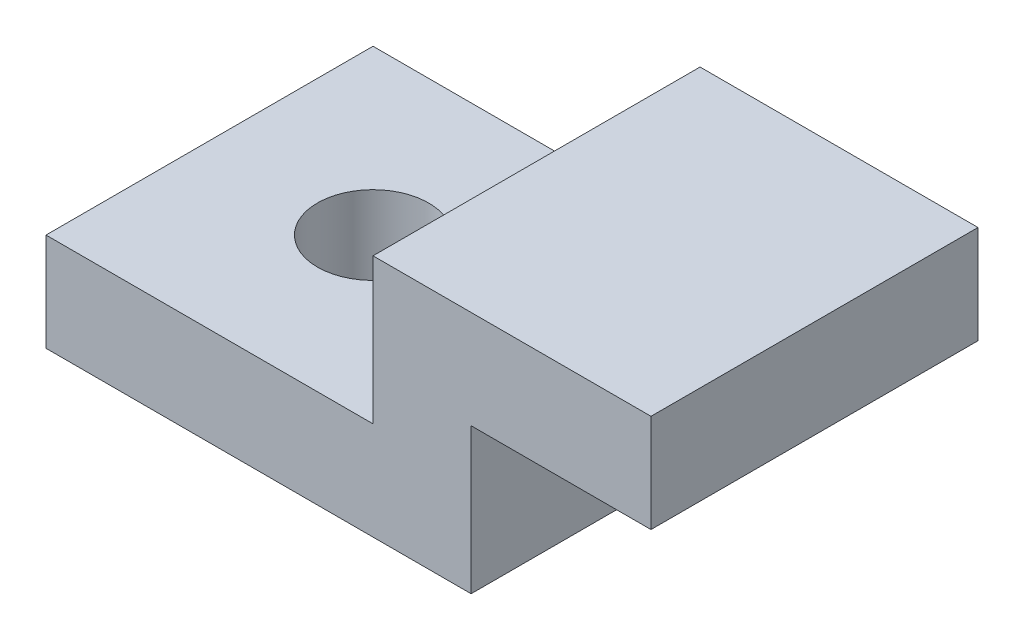
SolidWorks part; units mm, degrees
ref_plane "Front Plane" through (0, 0, 0) normal (0, 0, 1) x (1, 0, 0)
ref_plane "Top Plane" through (0, 0, 0) normal (0, 1, 0) x (1, 0, 0)
ref_plane "Right Plane" through (0, 0, 0) normal (1, 0, 0) x (0, 0, -1)
sketch "Sketch1" plane through (0, 0, 0) normal (0, 0, 1) x (1, 0, 0)
  line L1 (0, 0) -> (0, 4.45)
  line L2 (0, 4.45) -> (5.5, 4.45)
  line L3 (5.5, 4.45) -> (5.5, 7.45)
  line L4 (5.5, 7.45) -> (-3, 7.45)
  line L5 (-3, 7.45) -> (-3, 3)
  line L8 (-3, 0) -> (0, 0)
  line L9 (-3, 0) -> (-13, 0)
  line L10 (-13, 0) -> (-13, 3)
  line L11 (-13, 3) -> (-3, 3)
  dimension "D1" = 4.45
  dimension "D2" = 5.5
  dimension "D3" = 10
  dimension "D4" = 3
  dimension "D5" = 3
  dimension "D6" = 3
extrude "Boss-Extrude1" add sketch "Sketch1" along normal mid plane 10
sketch "Sketch2" plane through (0, 3, 0) normal (0, 1, 0) x (1, 0, 0)
  line L0 (-3, 5) -> (-13, 5) construction
  line L1 (-13, -5) -> (-13, 5) construction
  point P0 (-8, 0)
  point P3 (-8, 5)
  point P4 (0, 0)
  point P7 (-13, 0)
hole_wizard "M3 Clearance Hole1" positions "Sketch3" profile "Sketch4" hole size "M3" standard "ANSI Metric" end condition through all
sketch "Sketch3" plane through (0, 3, 0) normal (0, 1, 0) x (1, 0, 0)
  point P0 (-8, 0)
sketch "Sketch4" plane through (-8, 3, 0) normal (1, 0, 0) x (0, 0, 1)
  line L0 (0, 0) -> (0, 3)
  line L1 (0, 3) -> (1.7, 3)
  line L2 (1.7, 3) -> (1.7, 0)
  line L5 (1.7, 0) -> (0, 0)
  line L11 (0, -6.35) -> (0, 107.95) construction
  dimension "Thru Hole Dia." = 3.4
  dimension "Thru Hole Depth" = 3
